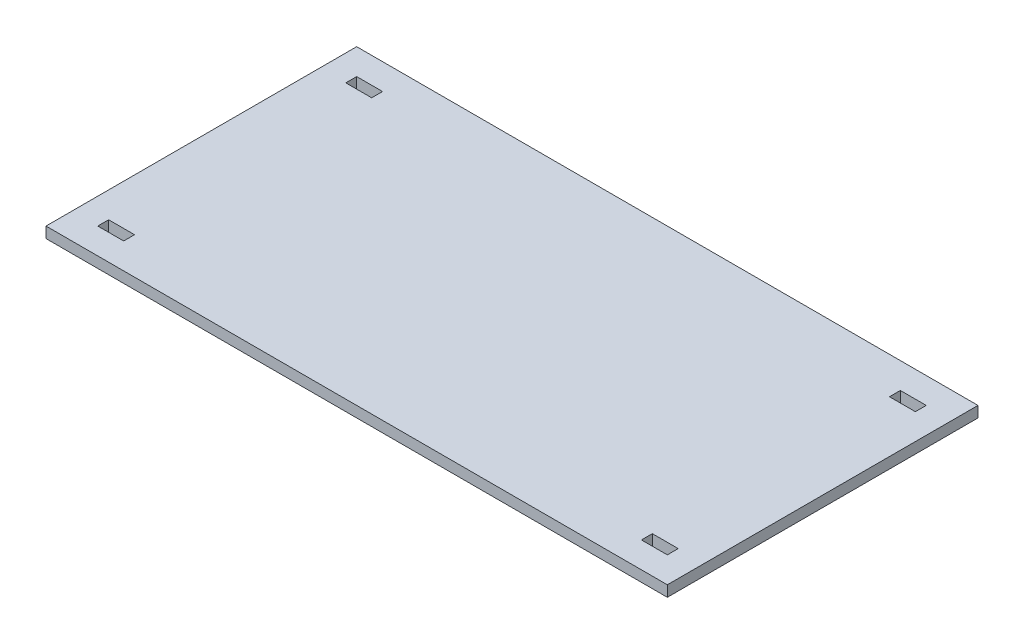
SolidWorks part; units mm, degrees
ref_plane "Front Plane" through (0, 0, 0) normal (0, 0, 1) x (1, 0, 0)
ref_plane "Top Plane" through (0, 0, 0) normal (0, 1, 0) x (1, 0, 0)
ref_plane "Right Plane" through (0, 0, 0) normal (1, 0, 0) x (0, 0, -1)
sketch "Sketch1" plane through (0, 0, 0) normal (0, 1, 0) x (1, 0, 0)
  line L1 (-216.1549, 23.7753) -> (88.6451, 23.7753)
  line L2 (-216.1549, 23.7753) -> (-216.1549, -128.6247)
  line L3 (-216.1549, -128.6247) -> (88.6451, -128.6247)
  line L4 (88.6451, 23.7753) -> (88.6451, -128.6247)
  dimension "D1" = 304.8
  dimension "D2" = 152.4
extrude "Boss-Extrude1" add sketch "Sketch1" along normal blind 5.334
sketch "Sketch4" plane through (0, 5.334, 0) normal (0, 1, 0) x (1, 0, 0)
  line L1 (63.2451, -110.5907) -> (75.9451, -110.5907)
  line L2 (63.2451, -110.5907) -> (63.2451, -115.9247)
  line L3 (63.2451, -115.9247) -> (75.9451, -115.9247)
  line L4 (75.9451, -110.5907) -> (75.9451, -115.9247)
  line L5 (-63.7549, 23.7753) -> (-63.7549, -128.6247) construction
  line L6 (88.6451, 23.7753) -> (-216.1549, 23.7753) construction
  line L7 (-216.1549, -128.6247) -> (88.6451, -128.6247) construction
  line L8 (88.6451, -52.4247) -> (-216.1549, -52.4247) construction
  line L9 (88.6451, -128.6247) -> (88.6451, 23.7753) construction
  line L10 (-216.1549, 23.7753) -> (-216.1549, -128.6247) construction
  line L11 (-203.4549, -110.5907) -> (-203.4549, -115.9247)
  line L12 (-190.7549, -115.9247) -> (-203.4549, -115.9247)
  line L13 (-190.7549, -110.5907) -> (-190.7549, -115.9247)
  line L14 (-190.7549, -110.5907) -> (-203.4549, -110.5907)
  line L15 (75.9451, 5.7413) -> (75.9451, 11.0753)
  line L16 (63.2451, 11.0753) -> (75.9451, 11.0753)
  line L17 (63.2451, 5.7413) -> (63.2451, 11.0753)
  line L18 (63.2451, 5.7413) -> (75.9451, 5.7413)
  line L19 (-190.7549, 5.7413) -> (-203.4549, 5.7413)
  line L20 (-190.7549, 5.7413) -> (-190.7549, 11.0753)
  line L21 (-190.7549, 11.0753) -> (-203.4549, 11.0753)
  line L22 (-203.4549, 5.7413) -> (-203.4549, 11.0753)
  dimension "D1" = 5.334
  dimension "D2" = 12.7
  dimension "D3" = 12.7
  dimension "D4" = 12.7
extrude "Cut-Extrude1" cut sketch "Sketch4" against normal through all
